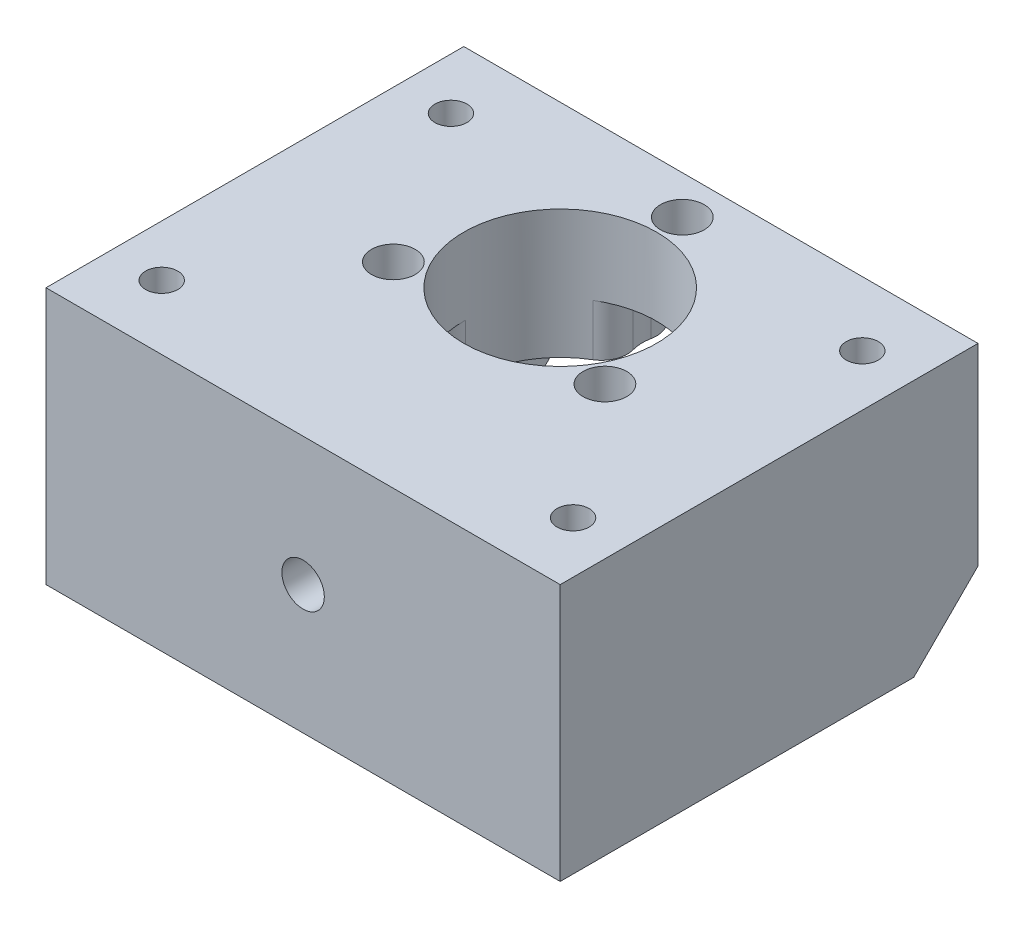
SolidWorks part; units mm, degrees
material "6061 Alloy"
ref_plane "Front Plane" through (0, 0, 0) normal (0, 0, 1) x (1, 0, 0)
ref_plane "Top Plane" through (0, 0, 0) normal (0, 1, 0) x (1, 0, 0)
ref_plane "Right Plane" through (0, 0, 0) normal (1, 0, 0) x (0, 0, -1)
sketch "Sketch3" plane through (0, 0, 0) normal (0, 1, 0) x (1, 0, 0)
  line L1 (-20, -12.5) -> (20, -12.5)
  line L2 (-20, -12.5) -> (-20, 12.5)
  line L3 (-20, 12.5) -> (20, 12.5)
  line L4 (20, -12.5) -> (20, 12.5)
  line L5 (-20, -12.5) -> (20, 12.5) construction
  line L6 (-20, 12.5) -> (20, -12.5) construction
  point P0 (0, 0)
  dimension "D1" = 25
  dimension "D2" = 40
extrude "Boss-Extrude2" add sketch "Sketch3" along normal mid plane 10
sketch "Sketch4" plane through (0, 5, 0) normal (0, 1, 0) x (1, 0, 0)
  circle A0 centre (0, 0) radius 7.5
  dimension "D1" = 15
extrude "Cut-Extrude2" cut sketch "Sketch4" against normal through all both
sketch "Sketch5" plane through (0, 5, 0) normal (0, -1, 0) x (1, 0, 0)
  line L0 (-20, -12.5) -> (-20, 12.5) construction
  line L1 (-20, 10) -> (20, 10)
  line L2 (-20, 10) -> (-20, 20)
  line L3 (-20, 20) -> (20, 20)
  line L4 (20, 10) -> (20, 20)
  line L5 (20, 12.5) -> (20, -12.5) construction
  dimension "D1" = 10
  dimension "D2" = 20
extrude "Boss-Extrude3" add sketch "Sketch5" along normal blind 20
hole_wizard "CBORE for M3 Hexagon socket head cap screws1" positions "Sketch6" profile "Sketch7" counterbore size "M3" standard "GB" end condition through all
sketch "Sketch6" plane through (0, -5, 0) normal (0, -1, 0) x (-1, 0, 0)
  line L0 (0, 0) -> (0, 9.5) construction
  point P7 (0, 9.5)
  point P18 (8.2272, -4.75)
  point P19 (-8.2272, -4.75)
  dimension "D1" = 9.5
  dimension "D2" = 3
sketch "Sketch7" plane through (0, -5, -9.5) normal (1, 0, 0) x (0, 0, -1)
  line L0 (0, 0) -> (0, 10)
  line L1 (0, 10) -> (1.7, 10)
  line L3 (1.7, 10) -> (1.7, 4)
  line L4 (1.7, 4) -> (3.1, 4)
  line L5 (3.1, 4) -> (3.1, 0)
  line L7 (3.1, 0) -> (0, 0)
  line L11 (0, -6.35) -> (0, 107.95) construction
  dimension "Thru Hole Dia." = 3.4
  dimension "Thru Hole Depth" = 10
  dimension "C'Bore Dia." = 6.2
  dimension "C'Bore Depth" = 4
fillet "Fillet1" radius 2 8 edges at (-5.1976, -3, 5.4069) (-7.2813, -3, 1.7978) (-2.0837, -3, -7.2047) (2.0837, -3, -7.2047) (-0.781, -3, -12.5) (0.781, -3, -12.5) (7.2813, -3, 1.7978) (5.1976, -3, 5.4069)
sketch "Sketch9" plane through (20, 0, 0) normal (1, 0, 0) x (0, 0, -1)
  line L0 (-10, -5) -> (-10, -15)
  line L2 (12.5, -5) -> (-10, -5)
  line L3 (-10, -15) -> (12.5, -15)
  line L4 (12.5, -15) -> (12.5, -5)
extrude "Boss-Extrude4" add sketch "Sketch9" against normal blind 8
mirror "Mirror1" about plane through (0, 0, 0) normal (1, 0, 0) of "Boss-Extrude4"
chamfer "Chamfer1" distance 5 angle 45 2 edges at (-16, -15, -12.5) (16, -15, -12.5)
hole_wizard "M3 Tapped Hole1" positions "Sketch12" profile "Sketch14" tap size "M3" standard "GB"
sketch "Sketch12" plane through (0, 5, 0) normal (0, 1, 0) x (1, 0, 0)
  line L0 (20, -20) -> (-20, -20) construction
  line L1 (-20, 12.5) -> (-20, -20) construction
  line L2 (20, 12.5) -> (-20, 12.5) construction
  line L3 (0, -5.5) -> (0, 5.5) construction
  point P0 (-16, 7.5)
  point P2 (-16, -15)
  point P14 (16, -15)
  point P15 (16, 7.5)
  dimension "D1" = 5
  dimension "D2" = 4
  dimension "D3" = 5
sketch "Sketch14" plane through (-16, 5, -7.5) normal (1, 0, 0) x (0, 0, 1)
  line L0 (0, 0) -> (0, 10.7511)
  line L1 (0, 10.7511) -> (1.25, 10)
  line L2 (1.25, 10) -> (1.25, 0)
  line L5 (1.25, 0) -> (0, 0)
  line L10 (0, 10.7511) -> (-1.25, 10) construction
  line L11 (0, -6.35) -> (0, 107.95) construction
  dimension "Tap Drill Dia." = 2.5
  dimension "Tap Drill Depth" = 10
  dimension "Drill Angle" = 118
cosmetic thread "Hole Thread1" parameters "D1"=6, "D2"=3
cosmetic thread "Hole Thread2" parameters "D1"=6, "D2"=3
cosmetic thread "Hole Thread3" parameters "D1"=6, "D2"=3
cosmetic thread "Hole Thread4" parameters "D1"=6, "D2"=3
fillet "Fillet2" radius 3 2 edges at (12, -10, 10) (-12, -10, 10)
hole_wizard "M4 Tapped Hole1" positions "Sketch15" profile "Sketch16" tap size "M4" standard "GB"
sketch "Sketch15" plane through (0, 0, 20) normal (0, 0, 1) x (1, 0, 0)
  line L0 (-20, 5) -> (20, -15) construction
  point P0 (0, -5)
sketch "Sketch16" plane through (0, -5, 20) normal (1, 0, 0) x (0, -1, 0)
  line L0 (0, 0) -> (0, 8.9914)
  line L1 (0, 8.9914) -> (1.65, 8)
  line L2 (1.65, 8) -> (1.65, 0)
  line L5 (1.65, 0) -> (0, 0)
  line L10 (0, 8.9914) -> (-1.65, 8) construction
  line L11 (0, -6.35) -> (0, 107.95) construction
  dimension "Tap Drill Dia." = 3.3
  dimension "Tap Drill Depth" = 8
  dimension "Drill Angle" = 118
cosmetic thread "Hole Thread5" parameters "D1"=8, "D2"=4
